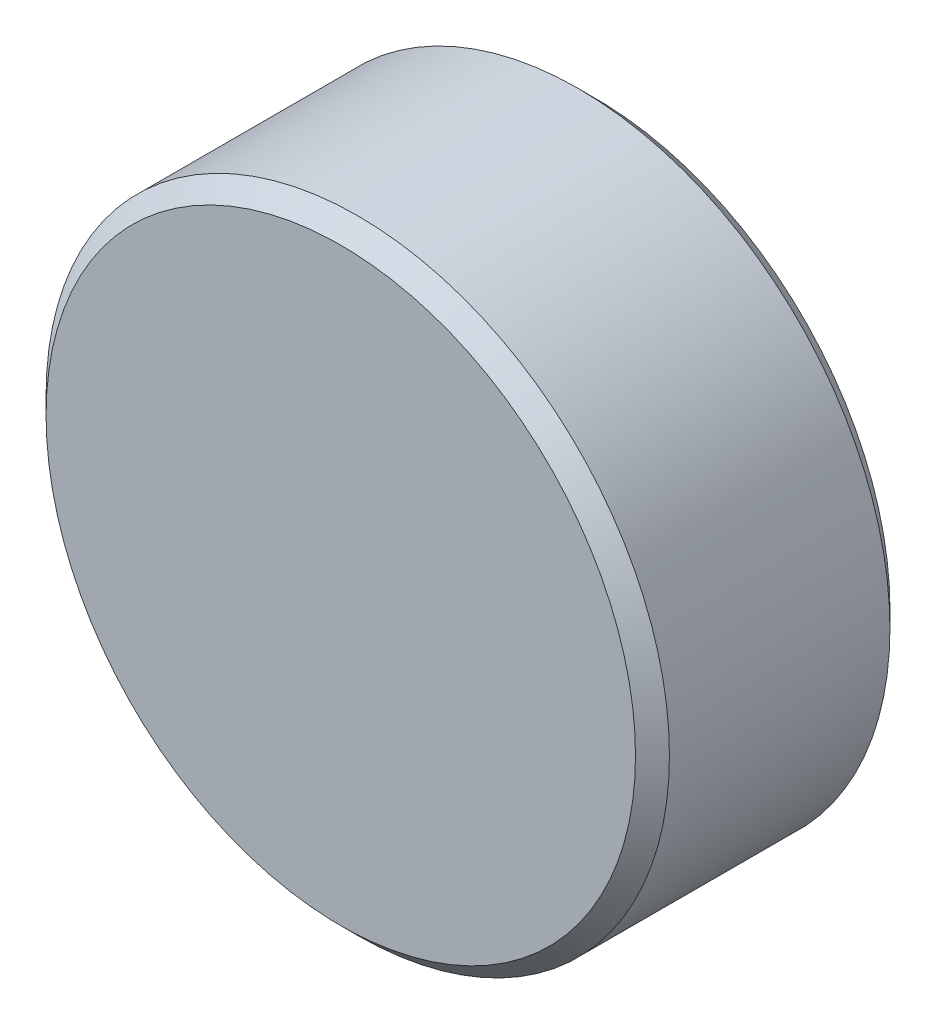
SolidWorks part; units mm, degrees
ref_plane "Plan de face" through (0, 0, 0) normal (0, 0, 1) x (1, 0, 0)
ref_plane "Plan de dessus" through (0, 0, 0) normal (0, 1, 0) x (1, 0, 0)
ref_plane "Plan de droite" through (0, 0, 0) normal (1, 0, 0) x (0, 0, -1)
sketch "Esquisse1" plane through (0, 0, 0) normal (0, 0, 1) x (1, 0, 0)
  circle A0 centre (0, 0) radius 36.75
extrude "Extrusion1" add sketch "Esquisse1" along normal blind 30
chamfer "Chanfrein1" distance 2 angle 45 1 edges at (36.75, 0, 30)
chamfer "Chanfrein2" distance 2 angle 45 1 edges at (36.75, 0, 0)
